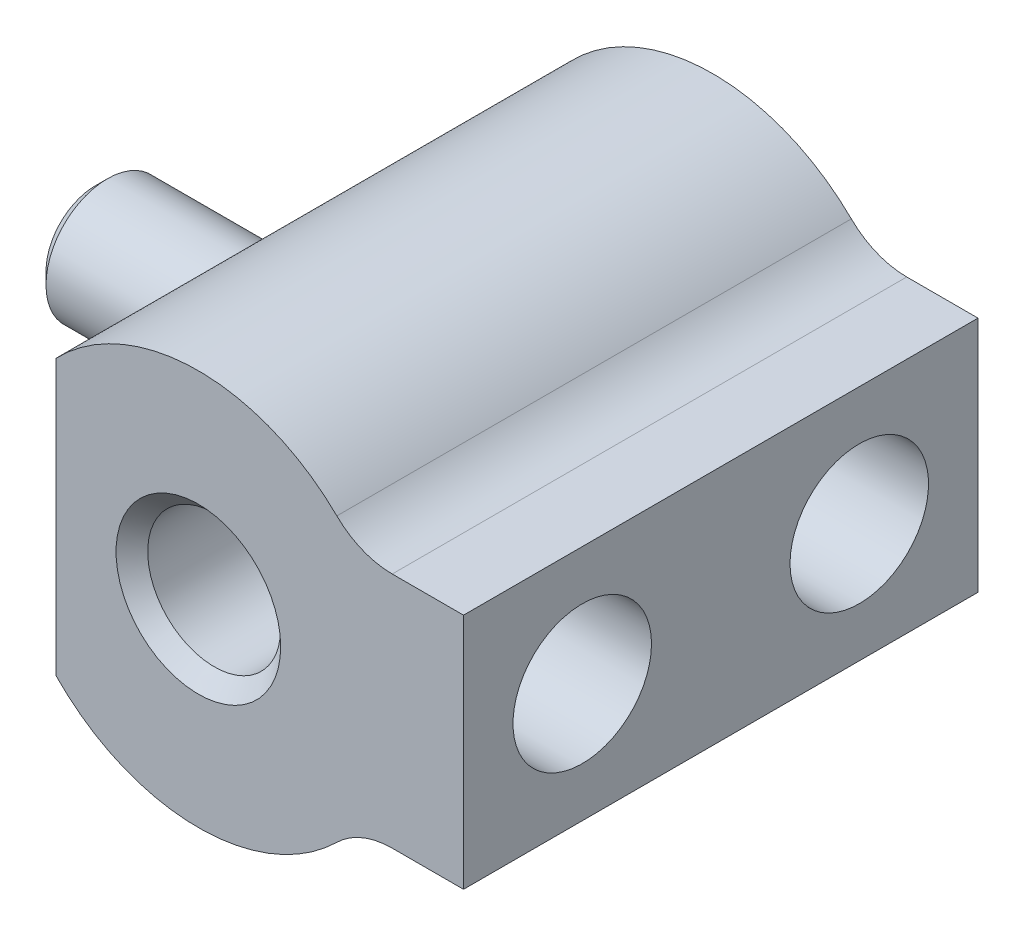
SolidWorks part; units mm, degrees
material "PLA2"
ref_plane "Front Plane" through (0, 0, 0) normal (0, 0, 1) x (1, 0, 0)
ref_plane "Top Plane" through (0, 0, 0) normal (0, 1, 0) x (1, 0, 0)
ref_plane "Right Plane" through (0, 0, 0) normal (1, 0, 0) x (0, 0, -1)
sketch "Sketch1" plane through (0, 0, 0) normal (0, 0, 1) x (1, 0, 0)
  circle A0 centre (0, 0) radius 2.1336
  circle A1 centre (0, 0) radius 6.35
  dimension "D1" = 4.2672
  dimension "D2" = 12.7
extrude "Boss-Extrude1" add sketch "Sketch1" along normal mid plane 16.51
sketch "Sketch3" plane through (0, 0, 8.255) normal (0, 0, 1) x (1, 0, 0)
  line L0 (-4.572, 4.4067) -> (-4.572, -4.4067)
  line L1 (0, 0.0885) -> (0, 50000.0885) construction
  line L3 (5.08, 3.81) -> (5.08, -3.81)
  line L4 (5.08, 0) -> (6.35, 0) construction
  arc A0 (-4.572, 4.4067) -> (-4.572, -4.4067) centre (0, 0) ccw
  arc A2 (5.08, -3.81) -> (5.08, 3.81) centre (0, 0) ccw
  circle A3 centre (0, 0) radius 6.35 construction
  point P1 (-6.35, 0)
  dimension "D1" = 1.778
  dimension "D2" = 1.27
extrude "Cut-Extrude1" cut sketch "Sketch3" against normal through all
sketch "Sketch4" plane through (-4.572, 0, 0) normal (-1, 0, 0) x (0, 0, 1)
  circle A0 centre (0, 0) radius 1.9685
  dimension "D1" = 3.937
extrude "Boss-Extrude2" add sketch "Sketch4" along normal blind 6.985
sketch "Sketch6" plane through (5.08, 0, 0) normal (1, 0, 0) x (0, 0, -1)
  line L4 (-8.255, 3.81) -> (-8.255, -3.81)
  line L5 (-8.255, -3.81) -> (8.255, -3.81)
  line L6 (8.255, -3.81) -> (8.255, 3.81)
  line L7 (8.255, 3.81) -> (-8.255, 3.81)
  line L8 (-8.255, 3.81) -> (-8.255, -3.81)
  line L9 (-8.255, -3.81) -> (8.255, -3.81)
  line L10 (8.255, -3.81) -> (8.255, 3.81)
  line L11 (8.255, 3.81) -> (-8.255, 3.81)
  dimension "D1" = 0
extrude "Boss-Extrude3" add sketch "Sketch6" along normal blind 3.429
fillet "Fillet1" radius 1.27 1 edges at (-4.572, 0, 1.9685)
chamfer "Chamfer1" distance 0.381 angle 45 1 edges at (-11.557, 0, 1.9685)
sketch "Sketch5" plane through (8.509, 0, 0) normal (1, 0, 0) x (0, 0, -1)
  line L0 (0, 0) -> (0, 50000) construction
  line L1 (-4.445, 0) -> (0, 0) construction
  circle A0 centre (-4.445, 0) radius 2.2225
  circle A1 centre (4.445, 0) radius 2.2225
  dimension "D1" = 4.445
  dimension "D2" = 8.89
extrude "Cut-Extrude2" cut sketch "Sketch5" against normal blind 8.255
chamfer "Chamfer2" distance 0.508 angle 45 2 edges at (2.1336, 0, -8.255) (2.1336, 0, 8.255)
fillet "Fillet2" radius 2.54 2 edges at (5.08, -3.81, 0) (5.08, 3.81, 0)
